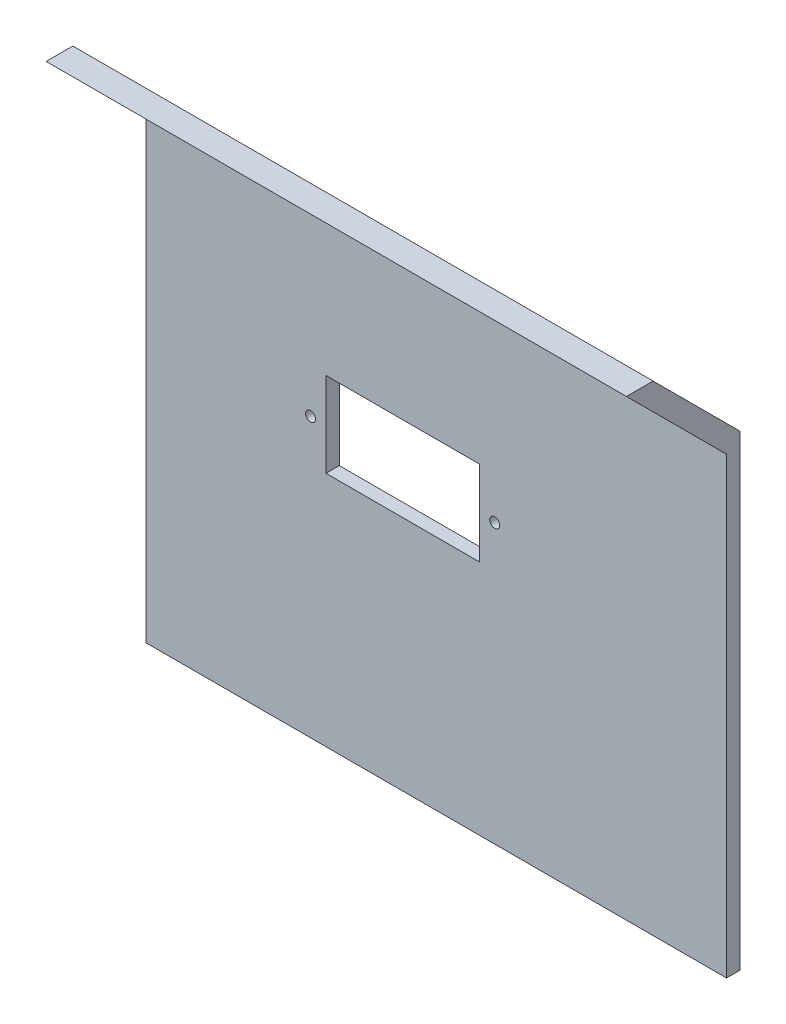
SolidWorks part; units mm, degrees
ref_plane "前视基准面" through (0, 0, 0) normal (0, 0, 1) x (1, 0, 0)
ref_plane "上视基准面" through (0, 0, 0) normal (0, 1, 0) x (1, 0, 0)
ref_plane "右视基准面" through (0, 0, 0) normal (1, 0, 0) x (0, 0, -1)
sketch "草图1" plane through (0, 0, 0) normal (0, 0, 1) x (1, 0, 0)
  line L1 (-85, -192.8808) -> (2, -192.8808)
  line L2 (-85, -192.8808) -> (-85, -122.8808)
  line L3 (-85, -122.8808) -> (2, -122.8808)
  line L4 (2, -192.8808) -> (2, -122.8808)
extrude "凸台-拉伸1" add sketch "草图1" along normal blind 2
sketch "草图3" plane through (2, 0, 0) normal (1, 0, 0) x (0, 0, -1)
  line L0 (-17, -109.8808) -> (-2, -124.8808)
  line L1 (-2, -192.8808) -> (-2, -122.8808) construction
  line L2 (-2, -124.8808) -> (0, -122.8808)
  line L3 (0, -122.8808) -> (-13, -109.8808)
  line L4 (-13, -109.8808) -> (-17, -109.8808)
extrude "凸台-拉伸2" add sketch "草图3" against normal up to surface (87 mm away) up to face at (-85, -157.8808, 1)
sketch "草图5" plane through (0, 0, 2) normal (0, 0, 1) x (1, 0, 0)
  line L0 (-41.5, -217.2043) -> (-41.5, -129.6225) construction
  line L1 (-85, -124.8808) -> (-85, -192.8808) construction
  line L2 (2, -192.8808) -> (2, -124.8808) construction
sketch "草图6" plane through (0, 0, 2) normal (0, 0, 1) x (1, 0, 0)
  line L14 (-41.5001, -144.8808) -> (-57.8501, -144.8808) construction
  line L15 (-58.0501, -144.6808) -> (-35.0501, -144.6808)
  line L16 (-58.0501, -144.6808) -> (-58.0501, -157.3808)
  line L17 (-58.0501, -157.3808) -> (-35.0501, -157.3808)
  line L18 (-35.0501, -144.6808) -> (-35.0501, -157.3808)
  line L19 (-41.5001, -157.3808) -> (-57.8501, -157.3808) construction
  line L20 (-35.2501, -151.1308) -> (-35.2501, -144.8808) construction
  line L21 (-57.8501, -157.3808) -> (-57.8501, -144.8808) construction
  dimension "D1" = 0.2
  dimension "D2" = 0
  dimension "D3" = 0.2
  dimension "D4" = 0.2
extrude "切除-拉伸1" cut sketch "草图6" against normal blind 15
sketch "草图7" plane through (0, 0, 2) normal (0, 0, 1) x (1, 0, 0)
  line L0 (-67.9302, -151.1308) -> (-19.8804, -151.1308) construction
  line L1 (-30.3501, -144.8808) -> (-35.2501, -144.8808) construction
  line L2 (-30.3501, -157.3808) -> (-35.2501, -157.3808) construction
  circle A0 centre (-32.7501, -151.1308) radius 0.75
  circle A1 centre (-60.3501, -151.1308) radius 0.75
  arc A2 (-31.5501, -150.6308) -> (-31.5501, -151.6308) centre (-32.7501, -151.1308) ccw construction
  dimension "D1" = 1.5
  dimension "D2" = 1.5
extrude "切除-拉伸2" cut sketch "草图7" against normal blind 15
sketch "草图8" plane through (0, -63.4404, 63.4404) normal (0, -0.7071, 0.7071) x (1, 0, 0)
  line L0 (-51.5, -79.7644) -> (-31.5, -79.7644) construction
  line L1 (-51.5, -75.7644) -> (-31.5, -75.7644)
  line L2 (-51.5, -83.7644) -> (-31.5, -83.7644)
  arc A0 (-51.5, -75.7644) -> (-51.5, -83.7644) centre (-51.5, -79.7644) ccw
  arc A1 (-31.5, -83.7644) -> (-31.5, -75.7644) centre (-31.5, -79.7644) ccw
  point P2 (-41.5, -79.7644)
  dimension "D1" = 8
  dimension "D2" = 20
extrude "切除-拉伸3" cut sketch "草图8" against normal blind 5
